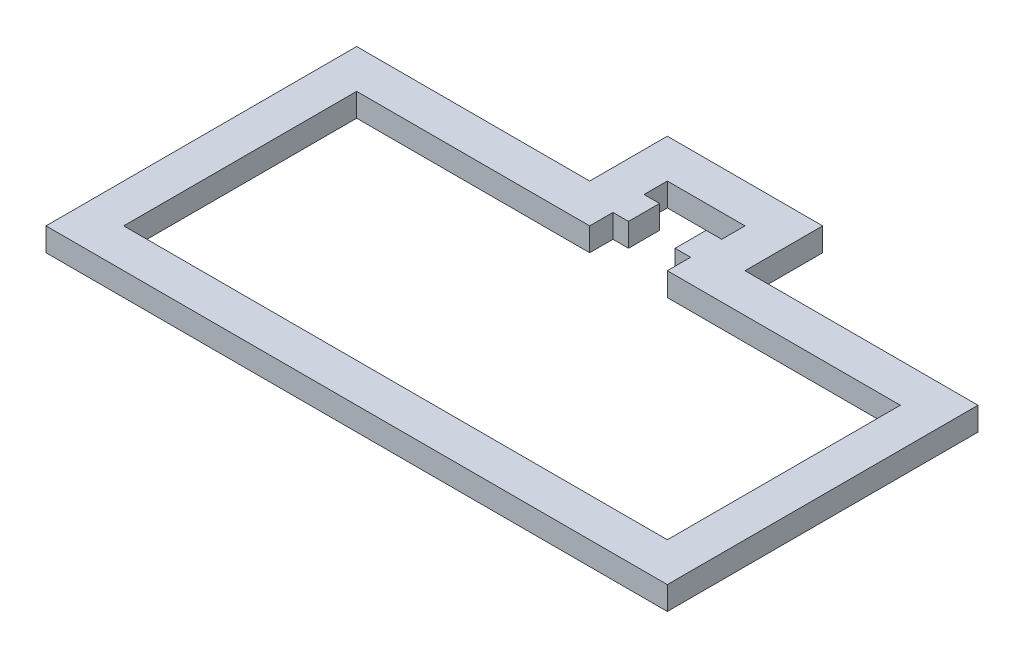
SolidWorks part; units mm, degrees
ref_plane "Front Plane" through (0, 0, 0) normal (0, 0, 1) x (1, 0, 0)
ref_plane "Top Plane" through (0, 0, 0) normal (0, 1, 0) x (1, 0, 0)
ref_plane "Right Plane" through (0, 0, 0) normal (1, 0, 0) x (0, 0, -1)
sketch "Sketch1" plane through (0, 0, 0) normal (0, 1, 0) x (1, 0, 0)
  line L1 (-399.8117, 165.1282) -> (400.1883, 165.1282)
  line L2 (-399.8117, 165.1282) -> (-399.8117, -234.8718)
  line L3 (-399.8117, -234.8718) -> (400.1883, -234.8718)
  line L4 (400.1883, 165.1282) -> (400.1883, -234.8718)
  line L5 (-349.8117, 115.1282) -> (350.1883, 115.1282)
  line L6 (-349.8117, 115.1282) -> (-349.8117, -184.8718)
  line L7 (-349.8117, -184.8718) -> (350.1883, -184.8718)
  line L8 (350.1883, 115.1282) -> (350.1883, -184.8718)
  line L17 (-49.8117, 215.1282) -> (50.1883, 215.1282)
  line L18 (-99.8117, 265.1282) -> (100.1883, 265.1282)
  line L19 (-99.8117, 265.1282) -> (-99.8117, 165.1282)
  line L20 (-99.8117, 165.1282) -> (100.1883, 165.1282)
  line L21 (100.1883, 265.1282) -> (100.1883, 165.1282)
  line L22 (-49.8117, 215.1282) -> (-49.8117, 115.1282)
  line L23 (-49.8117, 115.1282) -> (50.1883, 115.1282)
  line L24 (50.1883, 215.1282) -> (50.1883, 115.1282)
  line L25 (-49.8117, 145.1282) -> (-29.8117, 145.1282)
  line L26 (-49.8117, 145.1282) -> (-49.8117, 185.1282)
  line L27 (-49.8117, 185.1282) -> (-29.8117, 185.1282)
  line L28 (-29.8117, 145.1282) -> (-29.8117, 185.1282)
  line L29 (50.1883, 145.1282) -> (30.1883, 145.1282)
  line L30 (50.1883, 145.1282) -> (50.1883, 185.1282)
  line L31 (50.1883, 185.1282) -> (30.1883, 185.1282)
  line L32 (30.1883, 145.1282) -> (30.1883, 185.1282)
  dimension "D1" = 800
  dimension "D2" = 400
  dimension "D3" = 50
  dimension "D4" = 50
  dimension "D5" = 50
  dimension "D6" = 50
  dimension "D7" = 200
  dimension "D8" = 100
  dimension "D9" = 50
  dimension "D10" = 50
  dimension "D11" = 300
  dimension "D12" = 100
  dimension "D13" = 40
  dimension "D14" = 20
  dimension "D15" = 30
  dimension "D16" = 20
  dimension "D17" = 40
  dimension "D18" = 30
extrude "Boss-Extrude1" add sketch "Sketch1" along normal blind 30 contours L1 L24 L5 L8 L7 L6 L22 L2 L3 L4 | L17 L24 L1 L21 L18 L19 L22 | L27 L28 L25 L26 | L31 L32 L29 L30
equation "\"ScannerWidth\"= 800"
equation "\"ScannerLength\"= 400"
equation "\"SpineLength\"= 100"
equation "\"ScannerThickness\"= 50"
equation "\"D1@Sketch1\"=\"ScannerWidth\""
equation "\"D2@Sketch1\"=\"ScannerLength\""
equation "\"D3@Sketch1\"=\"ScannerThickness\""
equation "\"D4@Sketch1\"=\"ScannerThickness\""
equation "\"D5@Sketch1\"=\"ScannerThickness\""
equation "\"ScannerHeight\"= 30"
equation "\"SpineWidth\"= 100"
equation "\"D7@Sketch1\"=\"ScannerThickness\"*2+\"SpineWidth\""
equation "\"D6@Sketch1\"= \"ScannerThickness\""
equation "\"D9@Sketch1\"=\"ScannerThickness\""
equation "\"D8@Sketch1\"=\"SpineWidth\""
equation "\"D10@Sketch1\"=\"ScannerThickness\""
equation "\"D11@Sketch1\"=(\"ScannerWidth\"-\"SpineWidth\"-\"ScannerThickness\"*2)/2"
equation "\"TrainWidth\"= 40"
equation "\"TrainLength\"=20"
equation "\"D13@Sketch1\"= \"TrainWidth\""
equation "\"D14@Sketch1\"=\"TrainLength\""
equation "\"D15@Sketch1\"=(\"SpineLength\"-\"TrainWidth\")/2"
equation "\"D16@Sketch1\"=\"TrainLength\""
equation "\"D17@Sketch1\"=\"TrainWidth\""
equation "\"D18@Sketch1\"=(\"SpineLength\"-\"TrainWidth\")/2"
equation "\"D1@Boss-Extrude1\"=\"ScannerHeight\""
